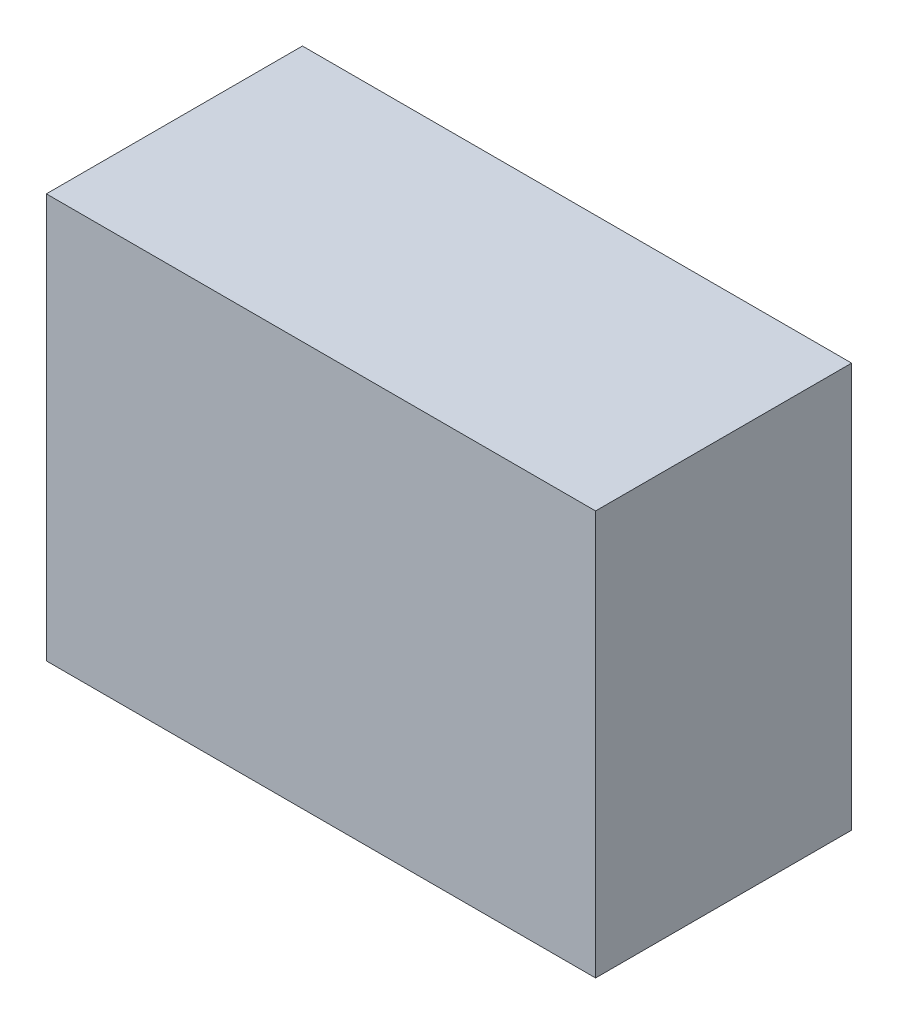
SolidWorks part; units mm, degrees
ref_plane "Front Plane" through (0, 0, 0) normal (0, 0, 1) x (1, 0, 0)
ref_plane "Top Plane" through (0, 0, 0) normal (0, 1, 0) x (1, 0, 0)
ref_plane "Right Plane" through (0, 0, 0) normal (1, 0, 0) x (0, 0, -1)
sketch "Sketch1" plane through (0, 0, 0) normal (0, 1, 0) x (1, 0, 0)
  line L1 (0, 0) -> (14.8, 0)
  line L2 (0, 0) -> (0, 6.9)
  line L3 (0, 6.9) -> (14.8, 6.9)
  line L4 (14.8, 0) -> (14.8, 6.9)
  dimension "D1" = 6.9
  dimension "D2" = 14.8
extrude "Boss-Extrude1" add sketch "Sketch1" along normal blind 10.9
